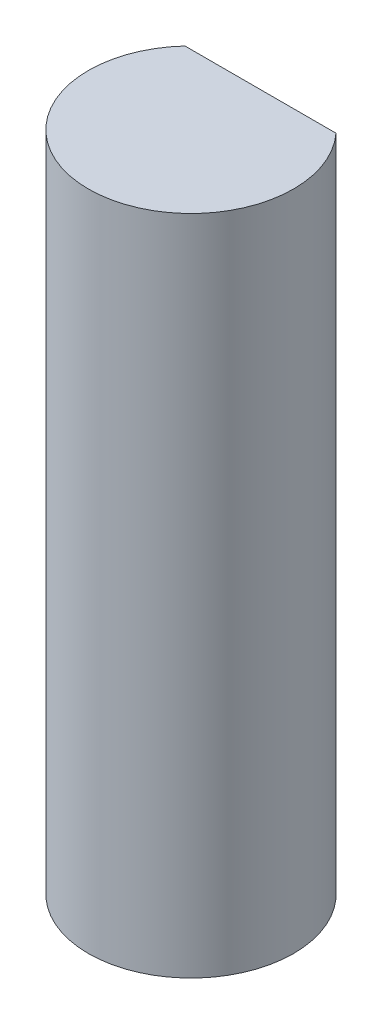
SolidWorks part; units mm, degrees
ref_plane "Спереди" through (0, 0, 0) normal (0, 0, 1) x (1, 0, 0)
ref_plane "Сверху" through (0, 0, 0) normal (0, 1, 0) x (1, 0, 0)
ref_plane "Справа" through (0, 0, 0) normal (1, 0, 0) x (0, 0, -1)
sketch "Эскиз1" plane through (0, 0, 0) normal (0, 1, 0) x (1, 0, 0)
  circle A0 centre (0, 0) radius 1.55
  dimension "D1" = 3.1
extrude "Бобышка-Вытянуть1" add sketch "Эскиз1" along normal blind 10
sketch "Эскиз3" plane through (0, 10, 0) normal (0, 1, 0) x (1, 0, 0)
  line L0 (-1.1402, 1.05) -> (1.1402, 1.05)
  circle A1 centre (0, 0) radius 1.55
  arc A2 (1.1402, 1.05) -> (-1.1402, 1.05) centre (0, 0) ccw
  dimension "D2" = 1.05
  dimension "D1" = 0
extrude "Вырез-Вытянуть1" cut sketch "Эскиз3" against normal blind 9
